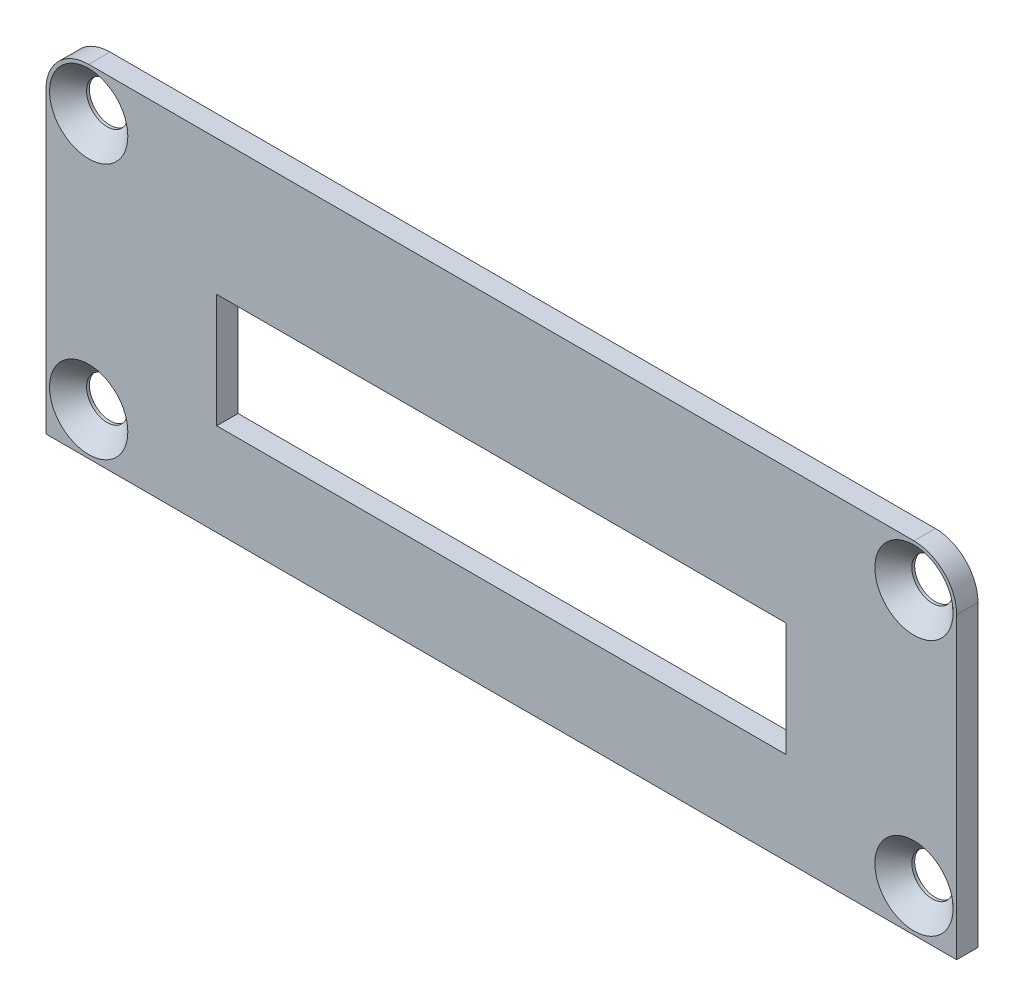
SolidWorks part; units mm, degrees
ref_plane "Front Plane" through (0, 0, 0) normal (0, 0, 1) x (1, 0, 0)
ref_plane "Top Plane" through (0, 0, 0) normal (0, 1, 0) x (1, 0, 0)
ref_plane "Right Plane" through (0, 0, 0) normal (1, 0, 0) x (0, 0, -1)
sketch "Sketch1" plane through (0, 0, 0) normal (0, 0, 1) x (1, 0, 0)
  line L1 (-32, 12) -> (32, 12)
  line L2 (-32, 12) -> (-32, -12)
  line L3 (-32, -12) -> (32, -12)
  line L4 (32, 12) -> (32, -12)
  line L5 (-32, 12) -> (32, -12) construction
  line L6 (-32, -12) -> (32, 12) construction
  point P0 (0, 0)
  dimension "D1" = 64
  dimension "D2" = 24
extrude "Boss-Extrude1" add sketch "Sketch1" against normal blind 1.5
sketch "Sketch2" plane through (0, 0, 0) normal (0, 0, 1) x (1, 0, 0)
  line L1 (-20, 2.5) -> (20, 2.5)
  line L2 (-20, 2.5) -> (-20, -5.5)
  line L3 (-20, -5.5) -> (20, -5.5)
  line L4 (20, 2.5) -> (20, -5.5)
  line L5 (-20, 2.5) -> (20, -5.5) construction
  line L6 (-20, -5.5) -> (20, 2.5) construction
  point P0 (0, -1.5)
  dimension "D1" = 1.5
  dimension "D2" = 40
  dimension "D3" = 8
extrude "Cut-Extrude1" cut sketch "Sketch2" against normal through all
fillet "Fillet1" radius 3 2 edges at (-32, 12, -0.75) (32, 12, -0.75)
hole_wizard "CSK for M2.5 Flat Head Machine Screw1" positions "Sketch4" profile "Sketch3" countersink size "M2.5" standard "ANSI Metric" end condition through all
sketch "Sketch4" plane through (0, 0, 0) normal (0, 0, 1) x (1, 0, 0)
  line L0 (29, 12) -> (-29, 12) construction
  line L1 (-32, 9) -> (-32, -12) construction
  line L2 (32, -12) -> (32, 9) construction
  line L3 (-32, -12) -> (32, -12) construction
  point P0 (-29, 9)
  point P8 (29, 9)
  point P14 (-29, -9)
  point P18 (29, -9)
  dimension "D1" = 3
  dimension "D2" = 3
  dimension "D3" = 3
  dimension "D4" = 3
sketch "Sketch3" plane through (-29, 9, 0) normal (1, 0, 0) x (0, -1, 0)
  line L0 (0, 0) -> (0, 1.5)
  line L1 (0, 1.5) -> (1.45, 1.5)
  line L2 (1.45, 1.5) -> (1.45, 1.3)
  line L3 (1.45, 1.3) -> (2.75, 0)
  line L5 (2.75, 0) -> (0, 0)
  line L6 (-1.45, 1.3) -> (-2.75, 0) construction
  line L11 (0, -6.35) -> (0, 107.95) construction
  dimension "Thru Hole Dia." = 2.9
  dimension "Thru Hole Depth" = 1.5
  dimension "Near C'Sink Dia." = 5.5
  dimension "Near C'Sink Angle" = 90
